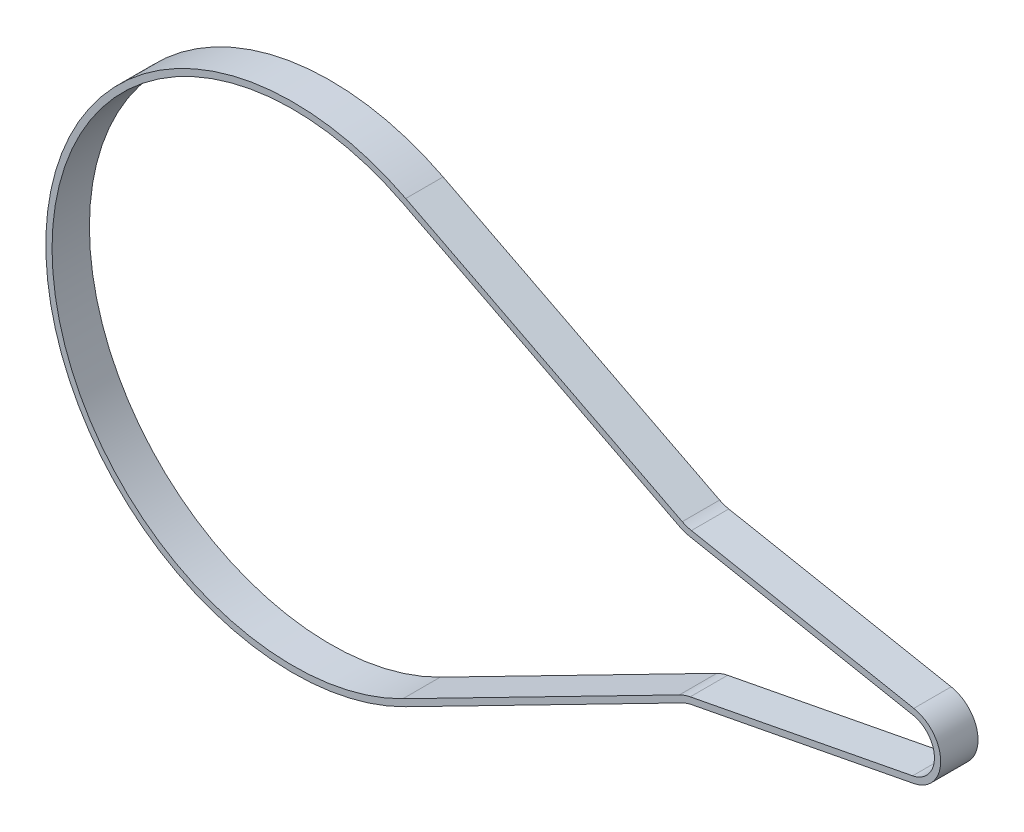
SolidWorks part; units mm, degrees
ref_plane "Front Plane" through (0, 0, 0) normal (0, 0, 1) x (1, 0, 0)
ref_plane "Top Plane" through (0, 0, 0) normal (0, 1, 0) x (1, 0, 0)
ref_plane "Right Plane" through (0, 0, 0) normal (1, 0, 0) x (0, 0, -1)
sketch "Sketch2" plane through (0, 0, 0) normal (0, 0, 1) x (1, 0, 0)
  line L0 (0, 0) -> (1, 0) construction
  line L1 (0, 0) -> (0, 1) construction
  line L2 (-1.2284, 28.6171) -> (34.4833, 21.7446)
  line L3 (34.4833, 13.2554) -> (-1.2284, 6.3829)
  line L4 (-2.9625, 5.7856) -> (-47.3612, -16.9482)
  line L5 (-47.3612, 51.9482) -> (-2.9625, 29.2144)
  arc A0 (-2.9625, 29.2144) -> (-1.2284, 28.6171) centre (0, 35) ccw
  arc A1 (34.4833, 21.7446) -> (34.4833, 13.2554) centre (33.6664, 17.5) cw
  arc A2 (-1.2284, 6.3829) -> (-2.9625, 5.7856) centre (0, 0) ccw
  arc A3 (-47.3612, -16.9482) -> (-47.3612, 51.9482) centre (-65, 17.5) cw
extrude "Extrude-Thin1" add sketch "Sketch2" along normal mid plane 6 thin thin type one direction wall 1
